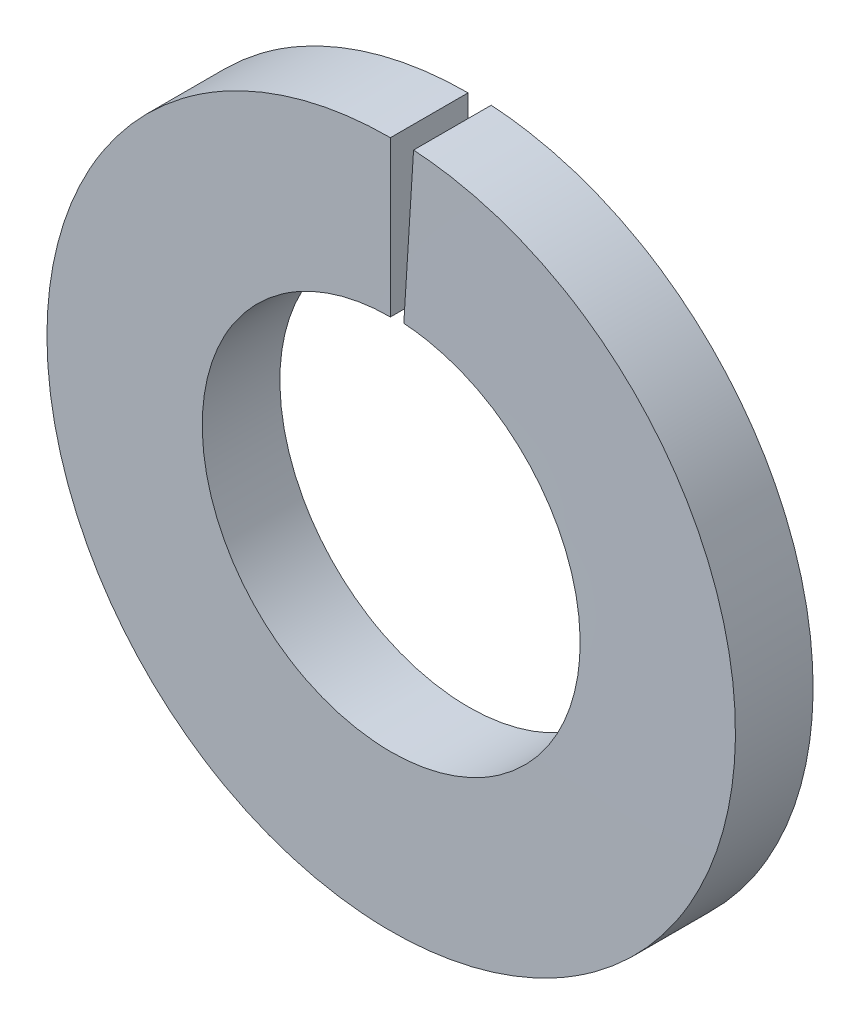
SolidWorks part; units mm, degrees
ref_plane "Front Plane" through (0, 0, 0) normal (0, 0, 1) x (1, 0, 0)
ref_plane "Top Plane" through (0, 0, 0) normal (0, 1, 0) x (1, 0, 0)
ref_plane "Right Plane" through (0, 0, 0) normal (1, 0, 0) x (0, 0, -1)
sketch "Sketch1" plane through (0, 0, 0) normal (0, 0, 1) x (1, 0, 0)
  line L0 (0, 3.1) -> (0, 1.7) construction
  circle A0 centre (0, 0) radius 3.1
  circle A1 centre (0, 0) radius 1.7 construction
  dimension "ID" = 3.4
  dimension "OD" = 6.2
curve "Helix/Spiral1" pitch 0.0141 height 0.014 turns 0.99 parameters "HT"=0.014
sketch "Sketch2" plane through (0, 0, 0) normal (1, 0, 0) x (0, 0, -1)
  line L1 (0, 3.1) -> (-0.7, 3.1)
  line L2 (0, 3.1) -> (0, 1.7)
  line L3 (0, 1.7) -> (-0.7, 1.7)
  line L4 (-0.7, 3.1) -> (-0.7, 1.7)
  dimension "THK" = 0.7
sweep "Sweep1" add profiles "Sketch2" path "Helix/Spiral1"
equation "\"HT@Helix/Spiral1\" = \"THK@Sketch2\" * .02"
